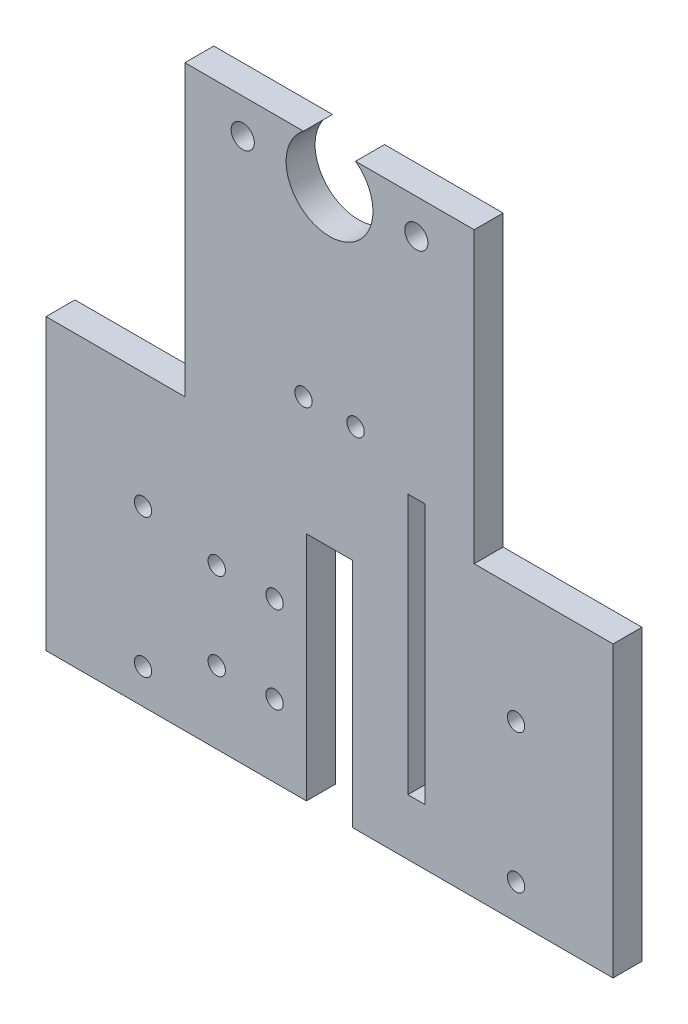
SolidWorks part; units mm, degrees
ref_plane "前视基准面" through (0, 0, 0) normal (0, 0, 1) x (1, 0, 0)
ref_plane "上视基准面" through (0, 0, 0) normal (0, 1, 0) x (1, 0, 0)
ref_plane "右视基准面" through (0, 0, 0) normal (1, 0, 0) x (0, 0, -1)
sketch "草图1" plane through (0, 0, 0) normal (0, 0, 1) x (1, 0, 0)
  line L0 (0, 50) -> (0, -50) construction
  line L1 (-25, 50) -> (25, 50)
  line L2 (-25, 50) -> (-25, 32.4243)
  line L3 (-25, -50) -> (25, -50)
  line L4 (25, 50) -> (25, 32.4243)
  line L5 (-25, 50) -> (25, -50) construction
  line L6 (-25, -50) -> (25, 50) construction
  line L7 (-25, 44) -> (25, 44) construction
  line L12 (-25, 32.4243) -> (-25, 0)
  line L13 (25, 32.4243) -> (25, 0)
  line L14 (-25, -50) -> (-49, -50)
  line L15 (-49, -50) -> (-49, 0)
  line L16 (-49, 0) -> (-25, 0)
  line L17 (25, -50) -> (49, -50)
  line L18 (49, -50) -> (49, 0)
  line L19 (49, 0) -> (25, 0)
  circle A0 centre (-15, 44) radius 2
  circle A1 centre (15, 44) radius 2
  point P0 (0, 0)
  dimension "D4" = 4
  dimension "D5" = 10
  dimension "D1" = 50
  dimension "D2" = 100
  dimension "D3" = 6
  dimension "D6" = 24
  dimension "D7" = 50
extrude "凸台-拉伸1" add sketch "草图1" along normal blind 5
sketch "草图2" plane through (0, 0, 5) normal (0, 0, 1) x (1, 0, 0)
  line L0 (-13, 44) -> (13, 44) construction
  circle A0 centre (-15, 44) radius 2 construction
  circle A1 centre (15, 44) radius 2 construction
  circle A2 centre (0, 44) radius 7.5
  dimension "D1" = 15
extrude "切除-拉伸1" cut sketch "草图2" against normal blind 10
sketch "草图3" plane through (0, 0, 0) normal (0, 0, -1) x (-1, 0, 0)
  line L0 (-4, -50) -> (4, -50)
  line L5 (0, -29.6407) -> (4, -10) construction
  line L6 (-4, -10) -> (0, -29.6407) construction
  line L8 (49, -50) -> (-49, -50) construction
  line L9 (4, -50) -> (4, -10)
  line L10 (4, -10) -> (-4, -10)
  line L11 (-4, -10) -> (-4, -50)
  point P0 (0, -29.6407)
  point P9 (0, -50)
  dimension "D1" = 8
  dimension "D2" = 40
extrude "切除-拉伸2" cut sketch "草图3" against normal through all
sketch "草图4" plane through (0, 0, 5) normal (0, 0, 1) x (1, 0, 0)
  line L13 (-39.735, -50) -> (-19.735, -50)
  line L14 (-49, -50) -> (-4, -50) construction
  line L15 (-39.735, -50) -> (-39.735, -46)
  line L16 (-39.735, -46) -> (-19.735, -46)
  line L17 (-19.735, -46) -> (-19.735, -50)
  line L18 (0, 0) -> (0, -54.8826) construction
  line L19 (39.735, -46) -> (19.735, -46)
  line L20 (39.735, -50) -> (39.735, -46)
  line L21 (39.735, -50) -> (19.735, -50)
  line L22 (19.735, -46) -> (19.735, -50)
  point P5 (-29.735, -50)
  dimension "D1" = 20
  dimension "D2" = 4
sketch "草图5" plane through (0, 0, 0) normal (0, 0, -1) x (-1, 0, 0)
  line L10 (-19.735, -46) -> (-19.735, -50) construction
  line L11 (-39.735, -50) -> (-19.735, -50) construction
  line L12 (-39.735, -46) -> (-19.735, -46) construction
  line L13 (-39.735, -50) -> (-39.735, -46) construction
  line L14 (-19.735, -46) -> (-19.735, -50)
  line L15 (-39.735, -50) -> (-19.735, -50)
  line L16 (-39.735, -46) -> (-19.735, -46)
  line L17 (-39.735, -50) -> (-39.735, -46)
  line L18 (0, 0) -> (0, -54.8826) construction
  line L19 (0, 0) -> (0, -54.8826) construction
  line L20 (39.735, -46) -> (19.735, -46)
  line L21 (39.735, -50) -> (39.735, -46)
  line L22 (39.735, -50) -> (19.735, -50)
  line L23 (19.735, -46) -> (19.735, -50)
sketch "草图6" plane through (0, 0, 0) normal (0, 0, -1) x (-1, 0, 0)
  line L0 (-29.735, -50) -> (-29.735, -14.1401) construction
  line L1 (-39.735, -50) -> (-19.735, -50) construction
  line L2 (-32.235, -44) -> (-27.235, -44) construction
  line L3 (-32.235, -20) -> (-27.235, -20) construction
  line L4 (0, 0) -> (0, -54.8826) construction
  line L5 (0, 0) -> (0, -54.8826) construction
  circle A2 centre (-32.235, -44) radius 1.5
  circle A3 centre (-32.235, -20) radius 1.5
  circle A5 centre (32.235, -44) radius 1.5
  circle A7 centre (32.235, -20) radius 1.5
  point P7 (-29.735, -44)
  point P11 (-29.735, -20)
  dimension "D2" = 3
  dimension "D5" = 5
  dimension "D6" = 3
  dimension "D1" = 5
  dimension "D3" = 6
  dimension "D4" = 24
extrude "切除-拉伸3" cut sketch "草图6" against normal through all
sketch "草图7" plane through (0, 0, 0) normal (0, 0, -1) x (-1, 0, 0)
  circle A0 centre (32.235, -44) radius 1.5 construction
  circle A2 centre (32.235, -20) radius 1.5 construction
  circle A5 centre (-32.235, -20) radius 1.5 construction
  circle A7 centre (-32.235, -44) radius 1.5 construction
  circle A8 centre (32.235, -44) radius 1.5
  circle A10 centre (32.235, -20) radius 1.5
  circle A13 centre (-32.235, -20) radius 1.5
  circle A15 centre (-32.235, -44) radius 1.5
  circle A16 centre (-32.235, -44) radius 4.5
  circle A17 centre (-32.235, -20) radius 4.5
  circle A18 centre (32.235, -20) radius 4.5
  circle A19 centre (32.235, -44) radius 4.5
  dimension "D1" = 3
extrude "切除-拉伸4" cut sketch "草图7" against normal blind 2
sketch "草图8" plane through (0, 0, 0) normal (0, 0, -1) x (-1, 0, 0)
  line L1 (-13.5359, 4.7103) -> (-16.5359, 4.7103)
  line L2 (-13.5359, 4.7103) -> (-13.5359, -40.2897)
  line L3 (-13.5359, -40.2897) -> (-16.5359, -40.2897)
  line L4 (-16.5359, 4.7103) -> (-16.5359, -40.2897)
  dimension "D1" = 3
  dimension "D2" = 45
extrude "切除-拉伸5" cut sketch "草图8" against normal through all
sketch "草图9" plane through (0, 0, 0) normal (0, 0, -1) x (-1, 0, 0)
  line L0 (0, 44) -> (0, 8.4078) construction
  line L1 (-17.5454, 10.25) -> (17.5454, 10.25) construction
  circle A0 centre (-4.5, 10.25) radius 1.5
  circle A1 centre (4.5, 10.25) radius 1.5
  point P7 (0, 10.25)
  dimension "D2" = 4.5
  dimension "D3" = 3
  dimension "D1" = 33.75
extrude "切除-拉伸6" cut sketch "草图9" against normal blind 10
sketch "草图10" plane through (0, 0, 0) normal (0, 0, -1) x (-1, 0, 0)
  line L0 (4, -30) -> (25, -30) construction
  line L1 (4, -50) -> (4, -10) construction
  line L4 (9.5, -37.5) -> (19.5, -37.5) construction
  line L5 (9.5, -37.5) -> (9.5, -22.5) construction
  line L6 (9.5, -22.5) -> (19.5, -22.5) construction
  line L7 (19.5, -37.5) -> (19.5, -22.5) construction
  line L8 (9.5, -37.5) -> (19.5, -22.5) construction
  line L9 (9.5, -22.5) -> (19.5, -37.5) construction
  circle A0 centre (9.5, -22.5) radius 1.5
  circle A1 centre (19.5, -22.5) radius 1.5
  circle A2 centre (19.5, -37.5) radius 1.5
  circle A3 centre (9.5, -37.5) radius 1.5
  point P4 (14.5, -30)
  point P7 (14.5, -30)
  dimension "D1" = 3
  dimension "D2" = 10
  dimension "D3" = 15
extrude "切除-拉伸7" cut sketch "草图10" against normal blind 10
